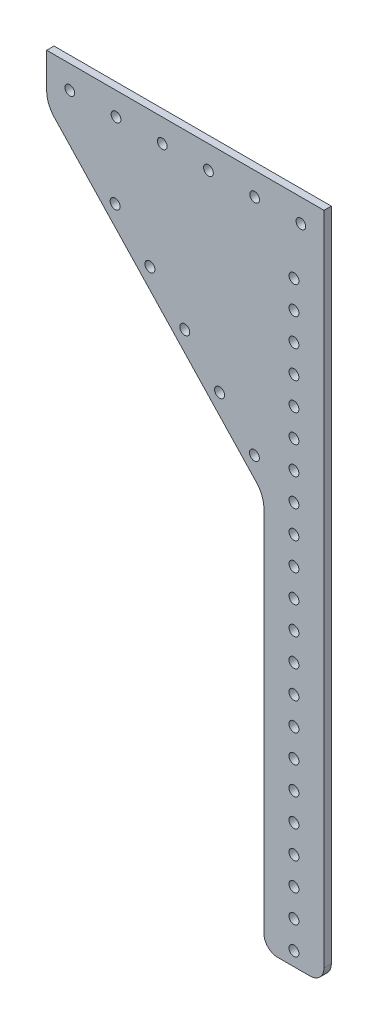
SolidWorks part; units mm, degrees
ref_plane "Front Plane" through (0, 0, 0) normal (0, 0, 1) x (1, 0, 0)
ref_plane "Top Plane" through (0, 0, 0) normal (0, 1, 0) x (1, 0, 0)
ref_plane "Right Plane" through (0, 0, 0) normal (1, 0, 0) x (0, 0, -1)
sketch "Sketch1" plane through (0, 0, 0) normal (0, 0, 1) x (1, 0, 0)
  line L0 (26, 290) -> (26, 0)
  line L1 (0, 0) -> (26, 0)
  line L2 (0, 0) -> (0, 270) construction
  line L5 (0, 270) -> (-94, 270) construction
  line L7 (26, 290) -> (-94, 290)
  line L8 (-94, 270) -> (-94, 290)
  line L9 (-94, 280) -> (26, 280) construction
  line L10 (-94, 270) -> (0, 170)
  line L11 (0, 170) -> (0, 0)
  line L12 (-85.7653, 270) -> (0, 178.7603) construction
  line L13 (-64.3815, 247.2513) -> (-79.4496, 263.2811) construction
  line L14 (13, 210) -> (13, 222) construction
  circle A0 centre (13, 6) radius 2.15
  circle A1 centre (13, 18) radius 2.15
  circle A2 centre (13, 30) radius 2.15
  circle A3 centre (13, 42) radius 2.15
  circle A4 centre (13, 54) radius 2.15
  circle A5 centre (13, 66) radius 2.15
  circle A6 centre (13, 78) radius 2.15
  circle A7 centre (13, 90) radius 2.15
  circle A8 centre (13, 102) radius 2.15
  circle A9 centre (13, 114) radius 2.15
  circle A10 centre (13, 126) radius 2.15
  circle A11 centre (13, 138) radius 2.15
  circle A12 centre (13, 150) radius 2.15
  circle A13 centre (13, 162) radius 2.15
  circle A14 centre (13, 174) radius 2.15
  circle A15 centre (13, 186) radius 2.15
  circle A16 centre (13, 198) radius 2.15
  circle A17 centre (13, 210) radius 2.15
  circle A19 centre (16, 280) radius 2.1
  circle A20 centre (-4, 280) radius 2.1
  circle A21 centre (-24, 280) radius 2.1
  circle A22 centre (-44, 280) radius 2.1
  circle A23 centre (-64, 280) radius 2.1
  circle A24 centre (-4.1095, 183.132) radius 2.15
  circle A25 centre (-19.1775, 199.1618) radius 2.15
  circle A26 centre (-34.2455, 215.1917) radius 2.15
  circle A27 centre (-49.3135, 231.2215) radius 2.15
  circle A28 centre (-64.3815, 247.2513) radius 2.15
  circle A29 centre (-79.4496, 263.2811) radius 2.15 construction
  circle A30 centre (13, 222) radius 2.15
  circle A31 centre (13, 234) radius 2.15
  circle A32 centre (13, 246) radius 2.15
  circle A33 centre (13, 258) radius 2.15
  circle A34 centre (13, 270) radius 2.15 construction
  circle A35 centre (-84, 280) radius 2.1
  dimension "D5" = 4.3
  dimension "D7" = 10
  dimension "D8" = 4.2
  dimension "D11" = 4.3
  dimension "D21" = 4.2
  dimension "D1" = 26
  dimension "D2" = 20
  dimension "D3" = 120
  dimension "D4" = 290
  dimension "D6" = 6
  dimension "D9" = 10
  dimension "D10" = 6
  dimension "D12" = 6
  dimension "D13" = 22
  dimension "D14" = 100
  dimension "D15" = 5
  dimension "D17" = 22
  dimension "D18" = 18
  dimension "D19" = 12
  dimension "D22" = 20
  dimension "D16" = 2
  dimension "D20" = 6
extrude "Boss-Extrude1" add sketch "Sketch1" along normal blind 3.175
fillet "Fillet2" radius 12 2 edges at (0, 170, 1.5875) (-94, 270, 1.5875)
fillet "Fillet3" radius 6 2 edges at (26, 0, 1.5875) (0, 0, 1.5875)
